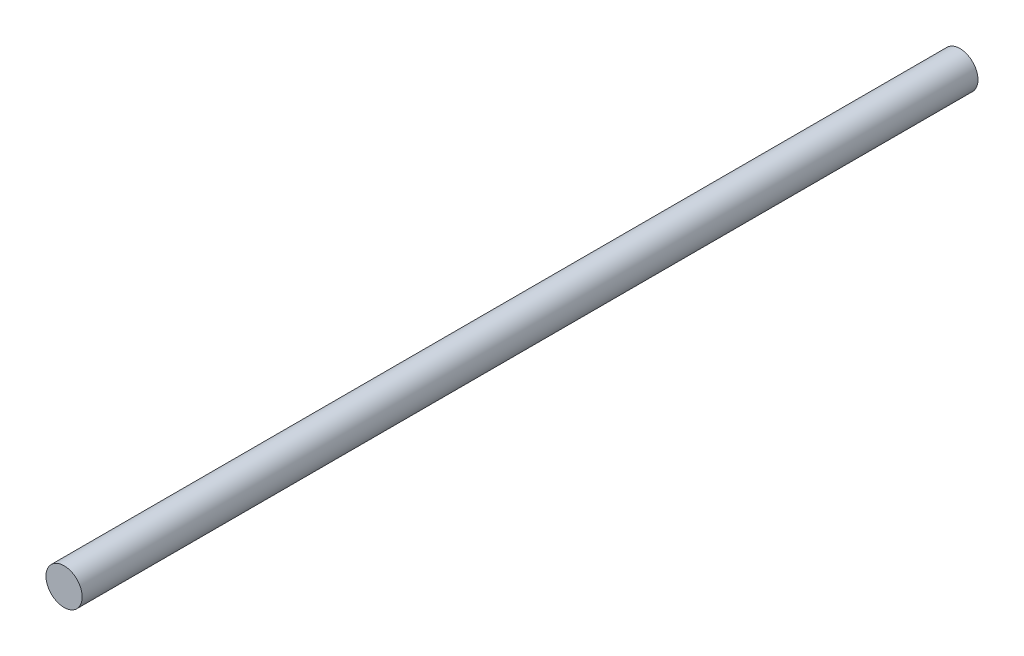
SolidWorks part; units mm, degrees
ref_plane "Front Plane" through (0, 0, 0) normal (0, 0, 1) x (1, 0, 0)
ref_plane "Top Plane" through (0, 0, 0) normal (0, 1, 0) x (1, 0, 0)
ref_plane "Right Plane" through (0, 0, 0) normal (1, 0, 0) x (0, 0, -1)
sketch "Sketch1" plane through (0, 0, 0) normal (0, 0, 1) x (1, 0, 0)
  circle A0 centre (0, 0) radius 4
  dimension "D1" = 8
extrude "Boss-Extrude1" add sketch "Sketch1" along normal blind 198
